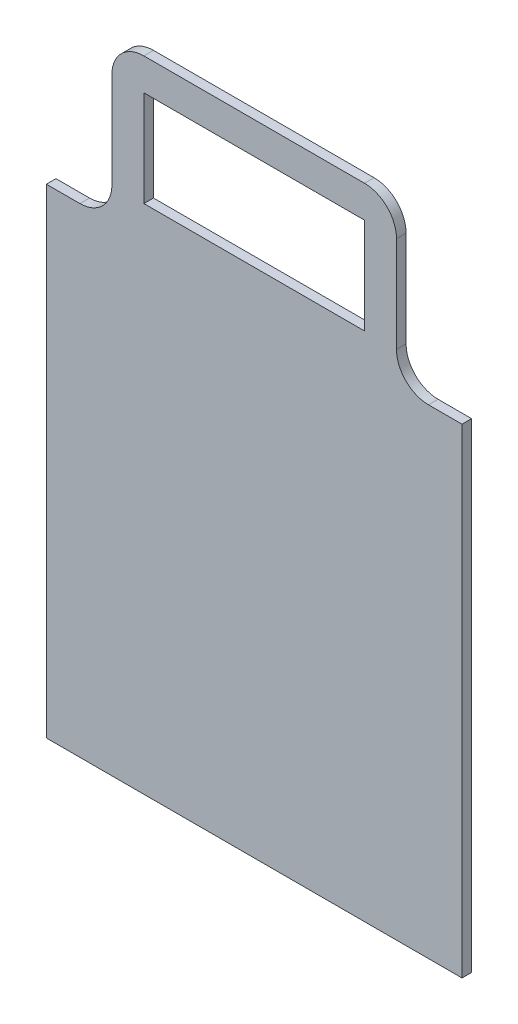
SolidWorks part; units mm, degrees
ref_plane "Front Plane" through (0, 0, 0) normal (0, 0, 1) x (1, 0, 0)
ref_plane "Top Plane" through (0, 0, 0) normal (0, 1, 0) x (1, 0, 0)
ref_plane "Right Plane" through (0, 0, 0) normal (1, 0, 0) x (0, 0, -1)
sketch "Sketch1" plane through (0, 0, 0) normal (0, 0, 1) x (1, 0, 0)
  line L0 (0, 85) -> (0, 75) construction
  line L1 (-65, 75) -> (-54.5, 75)
  line L2 (-65, 75) -> (-65, -75)
  line L3 (-65, -75) -> (65, -75)
  line L4 (65, 75) -> (65, -75)
  line L5 (-65, 75) -> (65, -75) construction
  line L6 (-65, -75) -> (65, 75) construction
  line L7 (-34.5, 85) -> (34.5, 85)
  line L8 (-34.5, 85) -> (-34.5, 115)
  line L9 (-34.5, 115) -> (34.5, 115)
  line L10 (34.5, 85) -> (34.5, 115)
  line L11 (-34.5, 85) -> (34.5, 115) construction
  line L12 (-34.5, 115) -> (34.5, 85) construction
  line L14 (44.5, 85) -> (44.5, 115)
  line L15 (34.5, 125) -> (-34.5, 125)
  line L16 (-44.5, 85) -> (-44.5, 115)
  line L17 (44.5, 75) -> (-44.5, 125) construction
  line L18 (44.5, 125) -> (-44.5, 75) construction
  line L19 (34.5, 100) -> (44.5, 100) construction
  line L20 (0, 115) -> (0, 125) construction
  line L21 (-34.5, 100) -> (-44.5, 100) construction
  line L22 (54.5, 75) -> (65, 75)
  arc A0 (54.5, 75) -> (44.5, 85) centre (54.5, 85) cw
  arc A1 (44.5, 115) -> (34.5, 125) centre (34.5, 115) ccw
  arc A2 (-34.5, 125) -> (-44.5, 115) centre (-34.5, 115) ccw
  arc A3 (-54.5, 75) -> (-44.5, 85) centre (-54.5, 85) ccw
  point P0 (0, 0)
  point P5 (0, 100)
  point P7 (0, 100)
  point P24 (0, 0)
  point P25 (5.9311, 75)
  dimension "D6" = 10
  dimension "D1" = 130
  dimension "D2" = 150
  dimension "D3" = 10
  dimension "D4" = 30
  dimension "D5" = 69
extrude "Boss-Extrude1" add sketch "Sketch1" along normal blind 3
